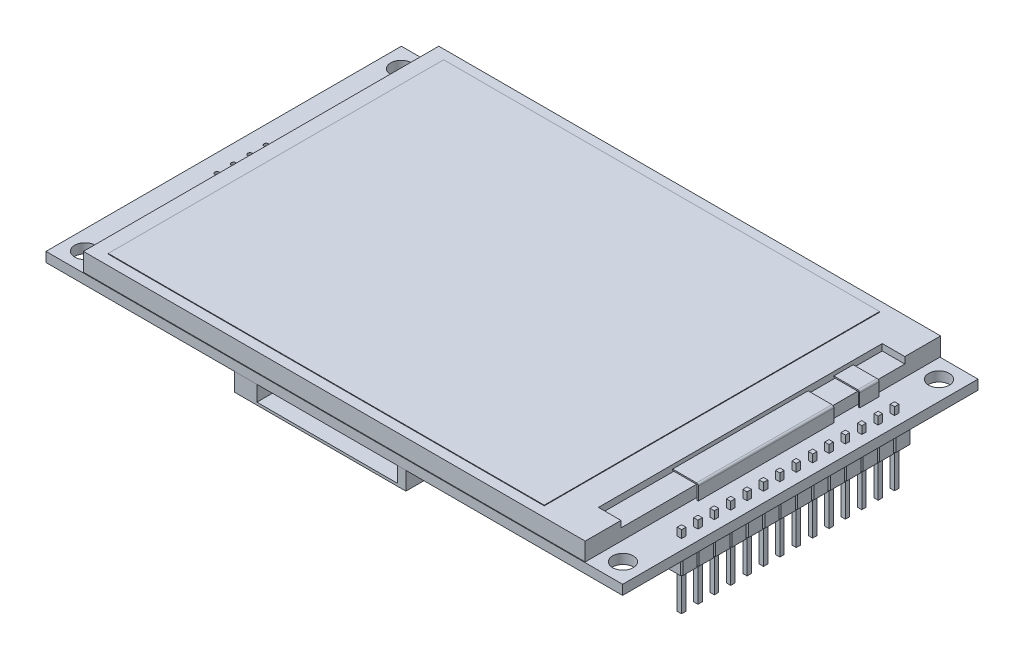
SolidWorks part; units mm, degrees
ref_plane "Ebene vorne" through (0, 0, 0) normal (0, 0, 1) x (1, 0, 0)
ref_plane "Ebene oben" through (0, 0, 0) normal (0, 1, 0) x (1, 0, 0)
ref_plane "Ebene rechts" through (0, 0, 0) normal (1, 0, 0) x (0, 0, -1)
sketch "Skizze1" plane through (0, 0, 0) normal (0, 1, 0) x (1, 0, 0)
  line L1 (-33.8, -26) -> (33.8, -26)
  line L2 (-33.8, -26) -> (-33.8, 26)
  line L3 (-33.8, 26) -> (33.8, 26)
  line L4 (33.8, -26) -> (33.8, 26)
  line L5 (-33.8, -26) -> (33.8, 26) construction
  line L6 (-33.8, 26) -> (33.8, -26) construction
  point P0 (0, 0)
  dimension "D1" = 52
  dimension "D2" = 67.6
extrude "Aufsatz-Linear austragen1" add sketch "Skizze1" along normal blind 0.1
sketch "Skizze2" plane through (0, 0, 0) normal (0, -1, 0) x (1, 0, 0)
  line L0 (55, 0) -> (-55, 0) construction
  line L1 (-36.1, -27.55) -> (41.7, -27.55)
  line L2 (-36.1, -27.55) -> (-36.1, 27.55)
  line L3 (-36.1, 27.55) -> (41.7, 27.55)
  line L4 (41.7, -27.55) -> (41.7, 27.55)
  line L6 (33.8, 26) -> (33.8, -26) construction
  point P4 (41.7, 0)
  dimension "D1" = 55.1
  dimension "D2" = 7.9
  dimension "D3" = 77.8
extrude "Aufsatz-Linear austragen2" add sketch "Skizze2" along normal blind 2.8 separate body
sketch "Skizze3" plane through (0, -2.8, 0) normal (0, -1, 0) x (1, 0, 0)
  line L0 (0.055, 0) -> (-0.055, 0) construction
  line L1 (-41.9, 27.55) -> (47.5, 27.55)
  line L2 (-41.9, 27.55) -> (-41.9, -27.55)
  line L3 (-41.9, -27.55) -> (47.5, -27.55)
  line L4 (47.5, 27.55) -> (47.5, -27.55)
  line L5 (41.7, 27.55) -> (-36.1, 27.55) construction
  line L6 (33.8, 26) -> (33.8, -26) construction
  point P4 (47.5, 0)
  dimension "D1" = 13.7
  dimension "D2" = 89.4
extrude "Aufsatz-Linear austragen3" add sketch "Skizze3" along normal blind 1.5 from offset 0.1 separate body
sketch "Skizze4" plane through (0, -2.9, 0) normal (0, 1, 0) x (1, 0, 0)
  line L0 (-1.595, 0) -> (1.595, 0) construction
  line L3 (47.5, 27.55) -> (47.5, -27.55) construction
  circle A0 centre (44.5, 24.5) radius 1.6
  circle A1 centre (44.5, -24.5) radius 1.6
  circle A2 centre (-38.9, -24.5) radius 1.6
  circle A3 centre (-38.9, 24.5) radius 1.6
  dimension "D1" = 3.2
  dimension "D2" = 49
  dimension "D3" = 24.5
  dimension "D4" = 83.4
  dimension "D5" = 3
extrude "Schnitt-Linear austragen1" cut sketch "Skizze4" against normal through all
sketch "Skizze6" plane through (0, -4.4, 0) normal (0, -1, 0) x (1, 0, 0)
  line L0 (46.7, 17.81) -> (46.9, 17.61)
  line L1 (44.5, 17.81) -> (46.7, 17.81)
  line L2 (44.3, 17.61) -> (44.3, 15.41)
  line L3 (44.5, 15.21) -> (46.7, 15.21)
  line L4 (46.9, 17.61) -> (46.9, 15.41)
  line L5 (44.3, 17.81) -> (46.9, 15.21) construction
  line L6 (44.3, 15.21) -> (46.9, 17.81) construction
  line L7 (44.3, 17.61) -> (44.5, 17.81)
  line L8 (44.3, 15.41) -> (44.5, 15.21)
  line L9 (46.9, 15.41) -> (46.7, 15.21)
  line L10 (1.595, 0) -> (-1.595, 0) construction
  line L11 (47.5, -27.55) -> (47.5, 27.55) construction
  point P0 (45.6, 16.51)
  dimension "D1" = 2.6
  dimension "D2" = 16.51
  dimension "D7" = 1.9
extrude "Aufsatz-Linear austragen4" add sketch "Skizze6" along normal blind 2.6
pattern_linear "Lineares Muster1" count 14 spacing 2.54 along (0, 0, -1) of "Aufsatz-Linear austragen4"
sketch "Skizze7" plane through (0, -7, 0) normal (0, -1, 0) x (1, 0, 0)
  line L0 (46.8, 17.71) -> (44.4, 15.31) construction
  line L1 (46.9, 17.61) -> (46.7, 17.81) construction
  line L3 (44.4, 17.71) -> (46.815, 15.325) construction
  line L4 (44.5, 17.81) -> (44.3, 17.61) construction
  line L5 (46.73, 15.24) -> (46.9, 15.41) construction
  line L7 (45.265, 16.175) -> (45.935, 16.175)
  line L8 (45.265, 16.175) -> (45.265, 16.845)
  line L9 (45.265, 16.845) -> (45.935, 16.845)
  line L10 (45.935, 16.175) -> (45.935, 16.845)
  line L11 (45.265, 16.175) -> (45.935, 16.845) construction
  line L12 (45.265, 16.845) -> (45.935, 16.175) construction
  line L13 (44.3, 15.41) -> (44.47, 15.24) construction
  point P12 (45.6, 16.51)
  dimension "D1" = 0.67
extrude "Aufsatz-Linear austragen5" add sketch "Skizze7" along normal blind 6 and the other way blind 5.3 separate body
pattern_linear "Lineares Muster3" count 14 spacing 2.54 along (0, 0, -1) of "Aufsatz-Linear austragen5"
sketch "Skizze8" plane through (0, -4.4, 0) normal (0, -1, 0) x (1, 0, 0)
  line L0 (1.595, 0) -> (-1.595, 0) construction
  line L5 (-41.9, 27.55) -> (-41.9, -27.55) construction
  circle A0 centre (-39.1, 3.81) radius 0.35
  dimension "D1" = 0.7
  dimension "D3" = 2.8
  dimension "D2" = 3.81
extrude "Schnitt-Linear austragen2" cut sketch "Skizze8" against normal through all
pattern_linear "Lineares Muster2" count 4 spacing 2.54 along (0, 0, -1) of "Schnitt-Linear austragen2"
sketch "Skizze9" plane through (0, -4.4, 0) normal (0, -1, 0) x (1, 0, 0)
  line L0 (13.9, 27.55) -> (13.9, 9.35)
  line L1 (47.5, 27.55) -> (-41.9, 27.55) construction
  line L2 (13.9, 9.35) -> (-10.5, 9.35)
  line L3 (-10.5, 9.35) -> (-10.5, 15.05)
  line L4 (-10.5, 15.05) -> (-12.7, 17.55)
  line L5 (-12.7, 17.55) -> (-12.7, 27.55)
  line L6 (-12.7, 27.55) -> (13.9, 27.55)
  line L7 (47.5, -27.55) -> (47.5, 27.55) construction
  dimension "D1" = 26.6
  dimension "D2" = 24.4
  dimension "D3" = 18.2
  dimension "D4" = 33.6
  dimension "D5" = 5.7
  dimension "D6" = 10
extrude "Aufsatz-Linear austragen6" add sketch "Skizze9" along normal blind 2.8 separate body
sketch "Skizze10" plane through (0, -4.4, 0) normal (0, -1, 0) x (1, 0, 0)
  line L0 (13.9, 27.55) -> (-12.7, 27.55) construction
  line L1 (12.6, 27.55) -> (-9.2, 27.55)
  line L2 (12.6, 27.55) -> (12.6, 13.55)
  line L3 (12.6, 13.55) -> (-9.2, 13.55)
  line L4 (-9.2, 27.55) -> (-9.2, 13.55)
  line L6 (-10.5, 15.05) -> (-10.5, 9.35) construction
  line L7 (13.9, 9.35) -> (13.9, 27.55) construction
  dimension "D1" = 14
  dimension "D2" = 1.3
  dimension "D3" = 1.3
extrude "Schnitt-Linear austragen3" cut sketch "Skizze10" along normal blind 2.4
sketch "Skizze11" plane through (0, -4.4, 0) normal (0, -1, 0) x (1, 0, 0)
  line L0 (47.5, 27.55) -> (-41.9, 27.55) construction
  line L1 (29.25, 5.35) -> (27.95, 5.35)
  line L2 (29.25, 5.35) -> (29.25, 2.35)
  line L3 (29.25, 2.35) -> (27.95, 2.35)
  line L4 (27.95, 5.35) -> (27.95, 2.35)
  line L5 (30, -2.2) -> (27, -2.2)
  line L6 (30, -2.2) -> (30, -3.5)
  line L7 (30, -3.5) -> (27, -3.5)
  line L8 (27, -2.2) -> (27, -3.5)
  line L9 (47.5, -27.55) -> (47.5, 27.55) construction
  point P8 (29.25, 3.85)
  point P11 (28.6, 2.35)
  point P14 (30, -2.85)
  point P15 (28.5, -3.5)
  dimension "D1" = 1.3
  dimension "D2" = 3
  dimension "D3" = 23.7
  dimension "D4" = 18.9
  dimension "D5" = 30.4
  dimension "D6" = 19
extrude "Aufsatz-Linear austragen7" add sketch "Skizze11" along normal blind 1 separate body
sketch "Skizze12" plane through (0, -4.4, 0) normal (0, -1, 0) x (1, 0, 0)
  line L0 (47.5, 27.55) -> (-41.9, 27.55) construction
  line L1 (32.45, 4.85) -> (31.55, 4.85)
  line L2 (32.45, 4.85) -> (32.45, 2.85)
  line L3 (32.45, 2.85) -> (31.55, 2.85)
  line L4 (31.55, 4.85) -> (31.55, 2.85)
  line L5 (25.65, 4.85) -> (24.75, 4.85)
  line L6 (25.65, 4.85) -> (25.65, 2.85)
  line L7 (25.65, 2.85) -> (24.75, 2.85)
  line L8 (24.75, 4.85) -> (24.75, 2.85)
  line L9 (25.65, -1.85) -> (24.75, -1.85)
  line L10 (25.65, -1.85) -> (25.65, -3.85)
  line L11 (25.65, -3.85) -> (24.75, -3.85)
  line L12 (24.75, -1.85) -> (24.75, -3.85)
  line L13 (32.45, -12.15) -> (31.55, -12.15)
  line L14 (32.45, -12.15) -> (32.45, -14.15)
  line L15 (32.45, -14.15) -> (31.55, -14.15)
  line L16 (31.55, -12.15) -> (31.55, -14.15)
  line L17 (30.85, -12.15) -> (29.95, -12.15)
  line L18 (30.85, -12.15) -> (30.85, -14.15)
  line L19 (30.85, -14.15) -> (29.95, -14.15)
  line L20 (29.95, -12.15) -> (29.95, -14.15)
  line L21 (3.9, -1.55) -> (3, -1.55)
  line L22 (3.9, -1.55) -> (3.9, -3.55)
  line L23 (3.9, -3.55) -> (3, -3.55)
  line L24 (3, -1.55) -> (3, -3.55)
  line L25 (1.6, -1.55) -> (0.7, -1.55)
  line L26 (1.6, -1.55) -> (1.6, -3.55)
  line L27 (1.6, -3.55) -> (0.7, -3.55)
  line L28 (0.7, -1.55) -> (0.7, -3.55)
  line L29 (-0.7, -1.55) -> (-1.6, -1.55)
  line L30 (-0.7, -1.55) -> (-0.7, -3.55)
  line L31 (-0.7, -3.55) -> (-1.6, -3.55)
  line L32 (-1.6, -1.55) -> (-1.6, -3.55)
  line L33 (47.5, -27.55) -> (47.5, 27.55) construction
  line L34 (34.0778, 3.85) -> (28.8209, 3.85) construction
  line L35 (29.25, 2.35) -> (29.25, 5.35) construction
  point P32 (3.45, -3.55)
  point P33 (1.15, -3.55)
  point P34 (-1.15, -3.55)
  point P35 (3.9, -2.55)
  point P40 (32, -14.15)
  point P41 (30.4, -14.15)
  point P42 (32.45, 3.85)
  point P43 (32.45, -13.15)
  point P48 (29.25, 3.85)
  point P49 (31.55, 3.85)
  point P50 (32, 2.85)
  point P51 (25.2, 2.85)
  point P55 (25.65, 3.85)
  point P56 (25.65, -2.85)
  dimension "D1" = 2
  dimension "D2" = 0.9
  dimension "D3" = 2.3
  dimension "D4" = 2.3
  dimension "D5" = 30.1
  dimension "D6" = 46.35
  dimension "D7" = 1.6
  dimension "D8" = 17
  dimension "D9" = 6.8
  dimension "D11" = 6.7
extrude "Aufsatz-Linear austragen8" add sketch "Skizze12" along normal blind 0.6 separate body
sketch "Skizze13" plane through (0, 0, 0) normal (0, 1, 0) x (1, 0, 0)
  line L0 (41.7, 27.55) -> (41.7, -27.55) construction
  line L1 (41.7, -22) -> (38.2, -22)
  line L2 (41.7, -22) -> (41.7, 22)
  line L3 (41.7, 22) -> (38.2, 22)
  line L4 (38.2, -22) -> (38.2, 22)
  line L5 (-7.205, 0) -> (7.205, 0) construction
  point P6 (41.7, 0)
  dimension "D1" = 44
  dimension "D2" = 3.5
extrude "Schnitt-Linear austragen4" cut sketch "Skizze13" against normal blind 1
sketch "Skizze14" plane through (0, 0, 0) normal (0, 0, 1) x (1, 0, 0)
  line L0 (38.2, -0.6) -> (38.2, -0.8)
  line L1 (38.2, -0.8) -> (41.9, -0.8)
  line L2 (42, -0.9) -> (42, -2.9)
  line L3 (42, -2.9) -> (42.2, -2.9)
  line L4 (42.2, -2.9) -> (42.2, -0.9)
  line L5 (41.9, -0.6) -> (38.2, -0.6)
  line L6 (38.2, -1) -> (38.2, 0) construction
  line L7 (41.7, -2.8) -> (41.7, 0) construction
  line L8 (41.7, -1) -> (38.2, -1) construction
  line L9 (47.5, -2.9) -> (-41.9, -2.9) construction
  arc A0 (41.9, -0.8) -> (42, -0.9) centre (41.9, -0.9) cw
  arc A1 (42.2, -0.9) -> (41.9, -0.6) centre (41.9, -0.9) ccw
  dimension "D1" = 0.2
  dimension "D4" = 0.1
  dimension "D2" = 0.5
  dimension "D3" = 0.2
extrude "Aufsatz-Linear austragen9" add sketch "Skizze14" along normal mid plane 21 separate body
sketch "Skizze15" plane through (0, 0, 0) normal (0, 0, 1) x (1, 0, 0)
  line L6 (38.2, -0.8) -> (41.9, -0.8)
  line L7 (38.2, -0.6) -> (38.2, -0.8)
  line L8 (41.9, -0.6) -> (38.2, -0.6)
  line L9 (42.2, -2.9) -> (42.2, -0.9)
  line L10 (38.2, -0.6) -> (38.2, -0.8)
  line L11 (42, -0.9) -> (42, -2.9)
  line L12 (38.2, -0.8) -> (41.9, -0.8)
  line L14 (41.9, -0.6) -> (38.2, -0.6)
  line L15 (42.2, -2.9) -> (42.2, -0.9)
  line L17 (42, -0.9) -> (42, -2.9)
  line L18 (42, -2.9) -> (42.2, -2.9)
  line L19 (42, -2.9) -> (42.2, -2.9)
  arc A2 (42.2, -0.9) -> (41.9, -0.6) centre (41.9, -0.9) ccw
  arc A3 (42, -0.9) -> (41.9, -0.8) centre (41.9, -0.9) ccw
  arc A4 (42.2, -0.9) -> (41.9, -0.6) centre (41.9, -0.9) ccw
  arc A5 (42, -0.9) -> (41.9, -0.8) centre (41.9, -0.9) ccw
  dimension "D1" = 0
extrude "Aufsatz-Linear austragen10" add sketch "Skizze15" against normal blind 3 from offset 14.5 separate body offset against normal yes
equation "\"D3@Skizze4\"=\"D2@Skizze4\"/2"
